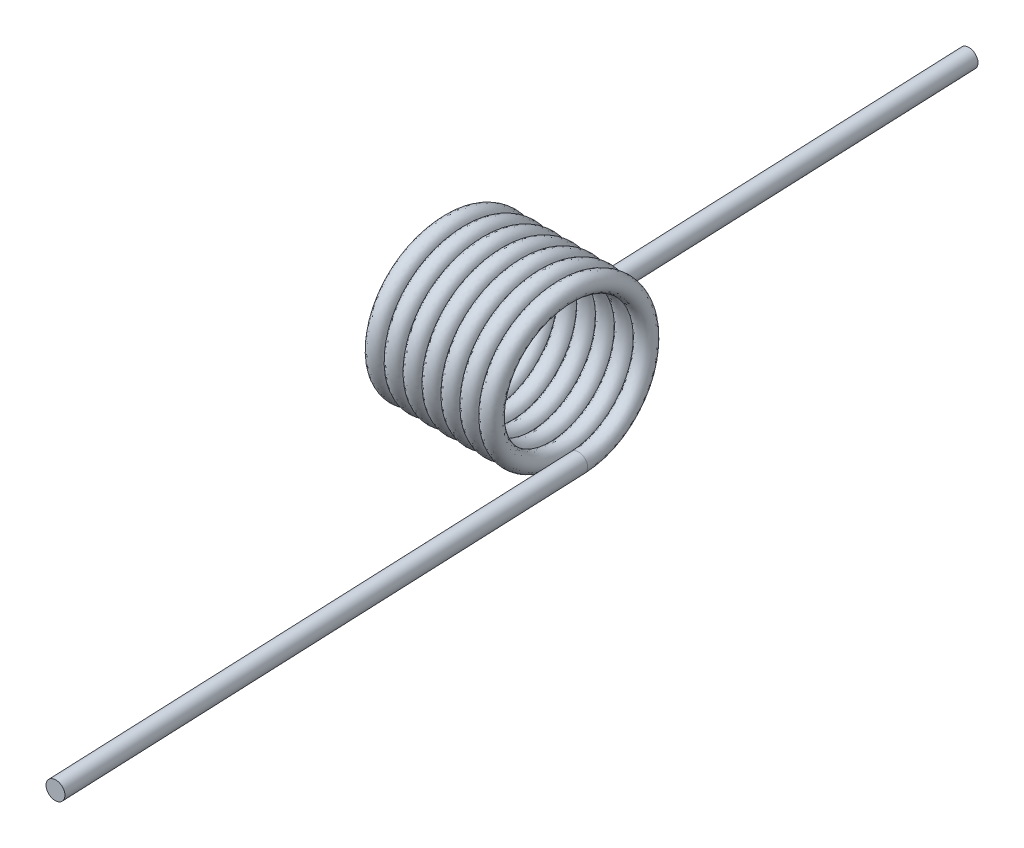
SolidWorks part; units mm, degrees
ref_plane "Front" through (0, 0, 0) normal (0, 0, 1) x (1, 0, 0)
ref_plane "Top" through (0, 0, 0) normal (0, 1, 0) x (1, 0, 0)
ref_plane "Right" through (0, 0, 0) normal (1, 0, 0) x (0, 0, -1)
sketch "Sketch1" plane through (0, 0, 0) normal (1, 0, 0) x (0, 0, -1)
  line L0 (0, -2.2098) -> (0, -2.8448) construction
  line L1 (0, -2.8448) -> (19.05, -2.8448) construction
  line L2 (0, -2.8448) -> (-19.05, -2.8448) construction
  line L3 (0, 0) -> (2.8448, 0) construction
  line L4 (0, 0) -> (0, -2.8448) construction
  line L5 (-19.05, -2.8448) -> (-19.05, -2.2098) construction
  line L6 (-19.05, -2.2098) -> (0, -2.2098) construction
  line L7 (19.05, -2.8448) -> (19.05, -2.2098) construction
  line L8 (19.05, -2.2098) -> (0, -2.2098) construction
  circle A0 centre (0, 0) radius 2.8448 construction
  circle A1 centre (0, 0) radius 1.778 construction
  circle A2 centre (0, 0) radius 2.5273 construction
  point P7 (0, -2.5273)
  point P10 (0, 2.8448)
  dimension "OD" = 5.6896
  dimension "For Shaft Diameter" = 3.556
  dimension "Wire Diameter" = 0.635
  dimension "Leg Length" = 19.05
  dimension "Deflection Angle" = 180
sketch "Sketch2" plane through (0, 0, 0) normal (1, 0, 0) x (0, 0, -1)
  circle A0 centre (0, 0) radius 2.5273 construction
  circle A2 centre (0, 0) radius 2.5273
curve "Helix/Spiral1" pitch 0.6604 height 4.6228 turns 7
ref_plane "Plane1" through (0, -2.5273, 0) normal (-0.0416, 0, -0.9991) x (0.9989, -0.0232, -0.0415)
sketch "Sketch3" plane through (0, -2.5273, 0) normal (-0.0416, 0, -0.9991) x (0.9989, -0.0232, -0.0415)
  circle A0 centre (0, 0) radius 0.3175
  dimension "D1" = 0.635
sweep "Sweep1" add profiles "Sketch3" path "Helix/Spiral1"
sketch "Sketch4" plane through (0, 0, 0) normal (0.0416, 0, 0.9991) x (-0.9989, 0.0232, 0.0415)
  circle A1 centre (-0.0587, 2.5266) radius 0.3175
  circle A2 centre (-0.0587, 2.5266) radius 0.3175
  dimension "D1" = 0
extrude "Extrude1" add sketch "Sketch4" along normal blind 19.05
sketch "Sketch5" plane through (-0.008, 0, -0.1919) normal (-0.0416, 0, -0.9991) x (0.9979, 0.0499, -0.0415)
  circle A1 centre (-4.7392, 2.2935) radius 0.3175
  circle A2 centre (-4.7392, 2.2935) radius 0.3175
  dimension "D1" = 0
extrude "Extrude2" add sketch "Sketch5" along normal blind 19.05
sketch "Sketch6" plane through (0, 0, 0) normal (1, 0, 0) x (0, 0, -1)
  circle A2 centre (0, 0) radius 2.2098 construction
equation "\"D4@Helix/Spiral1\" = \"Wire Diameter@Sketch1\" + .001"
equation "\"D1@Sketch3\"=\"Wire Diameter@Sketch1\""
equation "\"D1@Extrude2\"=\"Leg Length@Sketch1\""
equation "\"Leg Length@Extrude1\"=\"Leg Length@Sketch1\""
